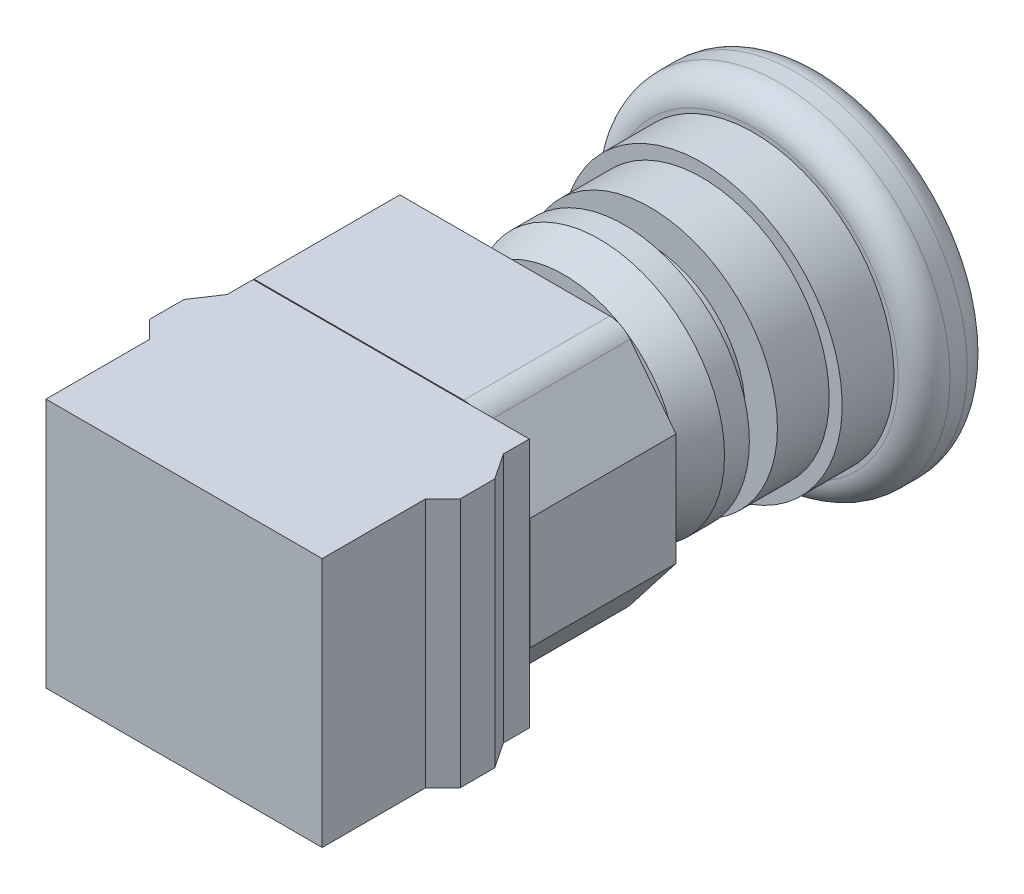
SolidWorks part; units mm, degrees
ref_plane "前视基准面" through (0, 0, 0) normal (0, 0, 1) x (1, 0, 0)
ref_plane "上视基准面" through (0, 0, 0) normal (0, 1, 0) x (1, 0, 0)
ref_plane "右视基准面" through (0, 0, 0) normal (1, 0, 0) x (0, 0, -1)
sketch "草图1" plane through (0, 0, 0) normal (0, 0, 1) x (1, 0, 0)
  line L1 (0, 0) -> (32, 0)
  line L2 (0, 0) -> (0, -29)
  line L3 (0, -29) -> (32, -29)
  line L4 (32, 0) -> (32, -29)
  dimension "D1" = 32
  dimension "D2" = 29
extrude "凸台-拉伸1" add sketch "草图1" along normal blind 12
sketch "草图2" plane through (0, 0, 0) normal (0, 1, 0) x (1, 0, 0)
  line L0 (0, 0) -> (-2, 2)
  line L1 (-2, 2) -> (-2, 6)
  line L2 (-2, 6) -> (0, 9)
  line L3 (0, 9) -> (0, 12)
  line L4 (0, -12) -> (0, 0) construction
  line L5 (32, 0) -> (0, 0) construction
  line L6 (32, 0) -> (0, 0)
  line L7 (32, 9) -> (32, 12)
  line L8 (34, 6) -> (32, 9)
  line L9 (34, 2) -> (34, 6)
  line L10 (32, 0) -> (34, 2)
  line L11 (0, 12) -> (29.3, 12)
  line L12 (16, 0) -> (16, 13.8485) construction
  line L13 (29.3, 12) -> (32, 12)
  dimension "D1" = 2
  dimension "D2" = 2
  dimension "D3" = 4
  dimension "D4" = 9
  dimension "D5" = 0
  dimension "D6" = 12
extrude "凸台-拉伸2" add sketch "草图2" against normal up to surface (29 mm away) up to face at (16, -29, 6)
sketch "草图3" plane through (0, 0, -12) normal (0, 0, -1) x (-1, 0, 0)
  line L0 (-25, 1) -> (0, 1)
  line L1 (-25, -30) -> (0, -30)
  line L2 (0, -29) -> (0, -30)
  line L3 (0, 0) -> (0, 1)
  line L4 (-25, -30) -> (-32, -21)
  line L5 (-32, -21) -> (-32, -8)
  line L6 (-32, -8) -> (-25, 1)
  line L7 (0, -29) -> (-32, -29) construction
  line L8 (-32, 0) -> (0, 0) construction
  line L9 (0, -29) -> (0, 0) construction
  circle A0 centre (-16, -14.5) radius 11
  line M1 (-32, -29) -> (0, -29)
  line M2 (0, -29) -> (0, 0)
  line M3 (0, 0) -> (-32, 0)
  line M5 (-32, 0) -> (-32, -29)
  dimension "D8" = 22
  dimension "D1" = 25
  dimension "D2" = 1
  dimension "D3" = 1
  dimension "D4" = 25
  dimension "D5" = 32
  dimension "D6" = 9
  dimension "D7" = 9
extrude "凸台-拉伸3" add sketch "草图3" along normal blind 17 contours L6 L4 A0 M5 M1 M2 M3
sketch "草图4" plane through (0, 0, -29) normal (0, 0, -1) x (-1, 0, 0)
  circle A0 centre (-16, -14.5) radius 11 construction
  circle A1 centre (-16, -14.5) radius 11
extrude "凸台-拉伸4" add sketch "草图4" along normal blind 3 separate body
sketch "草图5" plane through (0, 0, -32) normal (0, 0, -1) x (-1, 0, 0)
  circle A0 centre (-16, -14.5) radius 14.5
  dimension "D1" = 29
extrude "凸台-拉伸6" add sketch "草图5" along normal blind 10
sketch "草图6" plane through (0, 0, -42) normal (0, 0, -1) x (-1, 0, 0)
  circle A0 centre (-16, -14.5) radius 14.75
  dimension "D1" = 29.5
extrude "凸台-拉伸7" add sketch "草图6" along normal blind 6
sketch "草图7" plane through (0, 0, -48) normal (0, 0, -1) x (-1, 0, 0)
  circle A0 centre (-16, -14.5) radius 16.25
  dimension "D1" = 32.5
extrude "凸台-拉伸8" add sketch "草图7" along normal blind 6
sketch "草图8" plane through (0, 0, -54) normal (0, 0, -1) x (-1, 0, 0)
  circle A0 centre (-16, -14.5) radius 19.75
  dimension "D1" = 39.5
extrude "凸台-拉伸9" add sketch "草图8" along normal blind 8
sketch "草图9" plane through (0, 0, -42) normal (0, 0, 1) x (1, 0, 0)
  circle A0 centre (16, -14.5) radius 11
  circle A1 centre (16, -14.5) radius 22.5538
  dimension "D1" = 22
extrude "切除-拉伸1" cut sketch "草图9" along normal blind 3
chamfer "倒角1" distance 1.5 angle 70 1 edges at (1.5, -14.5, -32)
fillet "圆角1" radius 3 2 edges at (-3.75, -14.5, -54) (-3.75, -14.5, -62)
fillet "圆角2" radius 3 3 edges
sketch "草图10" plane through (0, 0, -12) normal (0, 0, -1) x (-1, 0, 0)
  line L0 (-32, -8) -> (-32, -21)
  line L1 (-24.3105, -29) -> (0, -29)
  line L2 (0, -29) -> (0, 0)
  line L3 (0, 0) -> (-24.3105, 0)
  line L4 (-32, -8) -> (-26.6786, -1.1582) construction
  line L5 (-26.6786, -27.8418) -> (-32, -21) construction
  line L6 (-26.6786, -27.8418) -> (-32, -21)
  line L7 (-32, -8) -> (-26.6786, -1.1582)
  line L8 (-31.9, -8.0343) -> (-31.9, -20.9657)
  line L9 (-26.5996, -27.7804) -> (-31.9, -20.9657)
  line L10 (-24.3105, -28.9) -> (-0.1, -28.9)
  line L11 (-0.1, -28.9) -> (-0.1, -0.1)
  line L12 (-0.1, -0.1) -> (-24.3105, -0.1)
  line L13 (-31.9, -8.0343) -> (-26.5996, -1.2196)
  arc A0 (-24.3105, 0) -> (-26.6786, -1.1582) centre (-24.3105, -3) ccw construction
  arc A1 (-26.6786, -27.8418) -> (-24.3105, -29) centre (-24.3105, -26) ccw construction
  arc A2 (-26.6786, -27.8418) -> (-24.3105, -29) centre (-24.3105, -26) ccw
  arc A3 (-24.3105, 0) -> (-26.6786, -1.1582) centre (-24.3105, -3) ccw
  arc A4 (-26.5996, -27.7804) -> (-24.3105, -28.9) centre (-24.3105, -26) ccw
  arc A5 (-24.3105, -0.1) -> (-26.5996, -1.2196) centre (-24.3105, -3) ccw
  dimension "D1" = 0.1
extrude "切除-拉伸2" cut sketch "草图10" along normal blind 0.1
sketch "草图11" plane through (0, 0, -62) normal (0, 0, -1) x (-1, 0, 0)
  line L0 (-32.75, -14.5) -> (0.75, -14.5) construction
  line L1 (-16, 2.25) -> (-16, -31.25) construction
  line L2 (-10.75, -5.4067) -> (-9.5, -3.2417)
  line L3 (-10.75, -5.4067) -> (-16, -14.5) construction
  line L6 (-4.25, -17.5) -> (-2, -14.5)
  line L7 (-2, -14.5) -> (-3, -14.5)
  line L8 (-5.5, -14.5) -> (-3, -14.5)
  line L9 (-4.25, -14.5) -> (-4.25, -19.3912) construction
  line L10 (-5.5, -14.5) -> (-6.5, -14.5)
  line L11 (-6.5, -14.5) -> (-4.25, -17.5)
  line L12 (-10.75, -23.5933) -> (-9.5, -25.7583)
  line L13 (-24.4731, -23.1758) -> (-23, -26.6244)
  line L14 (-23, -26.6244) -> (-22.5, -25.7583)
  line L15 (-21.25, -23.5933) -> (-22.5, -25.7583)
  line L16 (-21.25, -23.5933) -> (-20.75, -22.7272)
  line L17 (-20.75, -22.7272) -> (-24.4731, -23.1758)
  line L18 (-21.875, -24.6758) -> (-26.1109, -22.2302) construction
  line L19 (-26.5, -14.5) -> (-29, -14.5)
  line L20 (-19.2769, -2.8242) -> (-23, -2.3756)
  line L21 (-23, -2.3756) -> (-22.5, -3.2417)
  line L22 (-21.25, -5.4067) -> (-22.5, -3.2417)
  line L23 (-21.25, -5.4067) -> (-20.75, -6.2728)
  line L24 (-20.75, -6.2728) -> (-19.2769, -2.8242)
  line L25 (-21.875, -4.3242) -> (-17.6391, -1.8786) construction
  line L26 (-16, -14.5) -> (-6.5, -14.5) construction
  circle A0 centre (-16, -14.5) radius 16.75 construction
  arc A2 (-5.5, -14.5) -> (-10.75, -5.4067) centre (-16, -14.5) ccw
  arc A3 (-3, -14.5) -> (-9.5, -3.2417) centre (-16, -14.5) ccw
  arc A4 (-21.25, -23.5933) -> (-10.75, -23.5933) centre (-16, -14.5) ccw
  arc A5 (-22.5, -25.7583) -> (-9.5, -25.7583) centre (-16, -14.5) ccw
  arc A6 (-21.25, -5.4067) -> (-26.5, -14.5) centre (-16, -14.5) ccw
  arc A7 (-22.5, -3.2417) -> (-29, -14.5) centre (-16, -14.5) ccw
  dimension "D1" = 2.5
  dimension "D2" = 13
  dimension "D3" = 30
  dimension "D4" = 3
  dimension "D5" = 1
  dimension "D6" = 1
  dimension "D8" = 9.5
  dimension "D7" = 3
extrude "切除-拉伸3" cut sketch "草图11" against normal blind 0.3 contours L10 L11 L6 L7 L8 | L8 A3 L2 A2 | L15 A5 L12 A4 | L16 L17 L13 L14 L15 | L23 L24 L20 L21 L22 | L22 A7 L19 A6
